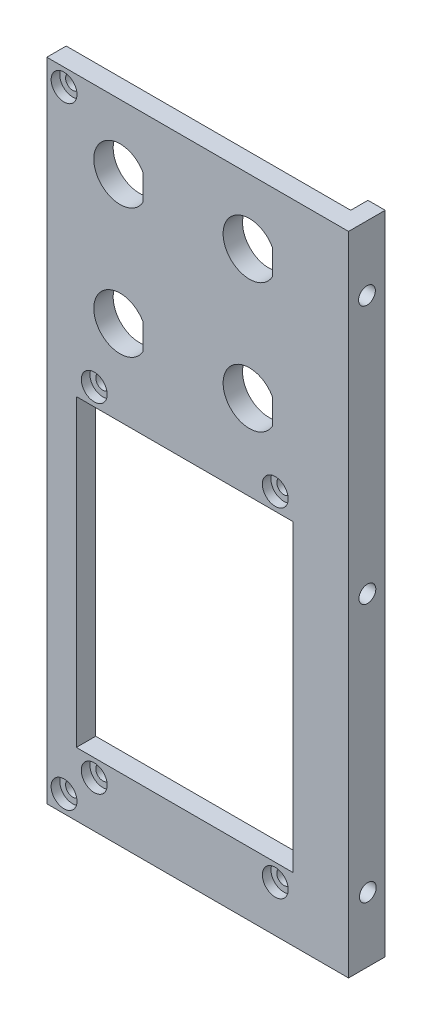
SolidWorks part; units mm, degrees
ref_plane "Front Plane" through (0, 0, 0) normal (1, 0, 0) x (0, 1, 0)
ref_plane "Top Plane" through (0, 0, 0) normal (0, 0, 1) x (0, 1, 0)
ref_plane "Right Plane" through (0, 0, 0) normal (0, 1, 0) x (-1, 0, 0)
sketch "Sketch1" plane through (0, 0, 0) normal (0, 0, 1) x (0, 1, 0)
  line L1 (0, 0) -> (150, 0)
  line L2 (0, 0) -> (0, 70)
  line L3 (0, 70) -> (150, 70)
  line L4 (150, 0) -> (150, 70)
  dimension "D1" = 150
  dimension "D2" = 70
extrude "Boss-Extrude1" add sketch "Sketch1" along normal blind 4.5
sketch "Sketch2" plane through (0, 0, 0) normal (0, 0, -1) x (1, 0, 0)
  line L0 (-38, 0) -> (-38, -150) construction
  line L1 (-70, 0) -> (0, 0) construction
  line L2 (0, -150) -> (-70, -150) construction
  line L4 (-12.85, -85.25) -> (-12.85, -14.75)
  line L5 (-12.85, -85.25) -> (-63.15, -85.25)
  line L6 (-12.85, -14.75) -> (-63.15, -14.75)
  line L7 (-63.15, -85.25) -> (-63.15, -14.75)
  line L8 (-12.85, -85.25) -> (-63.15, -14.75) construction
  line L9 (-12.85, -14.75) -> (-63.15, -85.25) construction
  line L10 (0, 0) -> (0, -150) construction
  point P9 (-38, -50)
  dimension "D1" = 38
  dimension "D2" = 50.3
  dimension "D3" = 50
  dimension "D4" = 70.5
extrude "Cut-Extrude1" cut sketch "Sketch2" against normal through all
sketch "Sketch3" plane through (0, 0, 4.5) normal (0, 0, 1) x (1, 0, 0)
  line L0 (-47.6887, 108) -> (-47.6887, 102)
  line L1 (-47.6887, 138) -> (-47.6887, 132)
  line L4 (-17.6887, 138) -> (-17.6887, 132)
  line L5 (-17.6887, 108) -> (-17.6887, 102)
  line L6 (-70, 105) -> (0, 105) construction
  line L7 (-70, 150) -> (-70, 0) construction
  line L8 (0, 0) -> (0, 150) construction
  line L9 (-70, 135) -> (0, 135) construction
  line L10 (0, 150) -> (-70, 150) construction
  arc A0 (-47.6887, 108) -> (-47.6887, 102) centre (-53, 105) ccw
  arc A1 (-47.6887, 138) -> (-47.6887, 132) centre (-53, 135) ccw
  arc A4 (-17.6887, 138) -> (-17.6887, 132) centre (-23, 135) ccw
  arc A5 (-17.6887, 108) -> (-17.6887, 102) centre (-23, 105) ccw
  dimension "D1" = 6.1
  dimension "D3" = 6.1
  dimension "D5" = 30
  dimension "D7" = 17
  dimension "D9" = 6.1
  dimension "D11" = 6.1
  dimension "D2" = 6
  dimension "D4" = 6
  dimension "D6" = 30
  dimension "D8" = 17
  dimension "D10" = 6
  dimension "D12" = 6
  dimension "D13" = 15
  dimension "D14" = 30
extrude "Cut-Extrude2" cut sketch "Sketch3" against normal through all
sketch "Sketch4" plane through (0, 0, 4.5) normal (0, 0, 1) x (1, 0, 0)
  line L0 (-38, 83.7306) -> (-38, 13.2306) construction
  line L1 (-59, 89.25) -> (-17, 89.25) construction
  line L2 (-59, 10.75) -> (-17, 10.75) construction
  line L3 (-63.15, 50) -> (-12.85, 50) construction
  line L6 (-63.15, 14.75) -> (-63.15, 85.25) construction
  line L7 (-59, 89.25) -> (-59, 10.75) construction
  line L8 (-17, 89.25) -> (-17, 10.75) construction
  line L9 (-12.85, 85.25) -> (-12.85, 14.75) construction
  line L11 (-66, 150) -> (-66, 0) construction
  line L12 (0, 150) -> (-70, 150) construction
  line L13 (-70, 0) -> (0, 0) construction
  line L14 (-70, 150) -> (-70, 0) construction
  circle A0 centre (-59, 89.25) radius 1.65
  circle A1 centre (-17, 89.25) radius 1.65
  circle A2 centre (-17, 10.75) radius 1.65
  circle A3 centre (-59, 10.75) radius 1.65
  circle A4 centre (-66, 146) radius 1.65
  circle A5 centre (-66, 4) radius 1.65
  point P1 (-38, 89.25)
  point P9 (-59, 50)
  point P16 (-38, 50)
  dimension "D3" = 3.3
  dimension "D1" = 42
  dimension "D2" = 78.5
  dimension "D4" = 4
  dimension "D5" = 4
  dimension "D6" = 4
extrude "Cut-Extrude3" cut sketch "Sketch4" against normal through all
sketch "Sketch5" plane through (0, 0, 4.5) normal (0, 0, 1) x (1, 0, 0)
  circle A0 centre (-59, 89.25) radius 3
  circle A1 centre (-17, 89.25) radius 3
  circle A2 centre (-17, 10.75) radius 3
  circle A3 centre (-59, 10.75) radius 3
  circle A4 centre (-66, 146) radius 3
  circle A5 centre (-66, 4) radius 3
  dimension "D1" = 6
extrude "Cut-Extrude4" cut sketch "Sketch5" against normal blind 2
sketch "Sketch7" plane through (0, 0, 0) normal (0, 0, -1) x (1, 0, 0)
  line L0 (-70, 0) -> (0, 0) construction
  line L1 (-4, 0) -> (0, 0)
  line L2 (-4, 0) -> (-4, -150)
  line L3 (-4, -150) -> (0, -150)
  line L4 (0, 0) -> (0, -150)
  dimension "D1" = 4
extrude "Boss-Extrude2" add sketch "Sketch7" along normal blind 4
sketch "Sketch8" plane through (0, 0, 0) normal (1, 0, 0) x (0, 1, 0)
  line L0 (0, 0) -> (150, 0.25) construction
  line L1 (150, 4.5) -> (150, -4) construction
  line L2 (0, 4.5) -> (0, -4) construction
  circle A0 centre (15, 0.025) radius 1.95
  circle A1 centre (75, 0.125) radius 1.95
  circle A2 centre (135, 0.225) radius 1.95
  dimension "D1" = 3.9
  dimension "D2" = 15
  dimension "D3" = 15
extrude "Cut-Extrude5" cut sketch "Sketch8" against normal blind 10
sketch "Sketch10" plane through (0, 0, 0) normal (0, 0, -1) x (1, 0, 0)
  line L0 (-63.15, -14.75) -> (-63.15, -85.25) construction
  line L3 (-44.5, -85.25) -> (-31.5, -85.25)
  line L4 (-44.5, -85.25) -> (-44.5, -130.25)
  line L5 (-31.5, -85.25) -> (-31.5, -130.25)
  line L6 (-44.5, -130.25) -> (-31.5, -130.25)
  line L7 (-63.15, -85.25) -> (-12.85, -85.25) construction
  point P10 (-38, -85.25)
  dimension "D1" = 13
  dimension "D2" = 45
  dimension "D3" = 25.15
extrude "Cut-Extrude6" cut sketch "Sketch10" against normal blind 1
